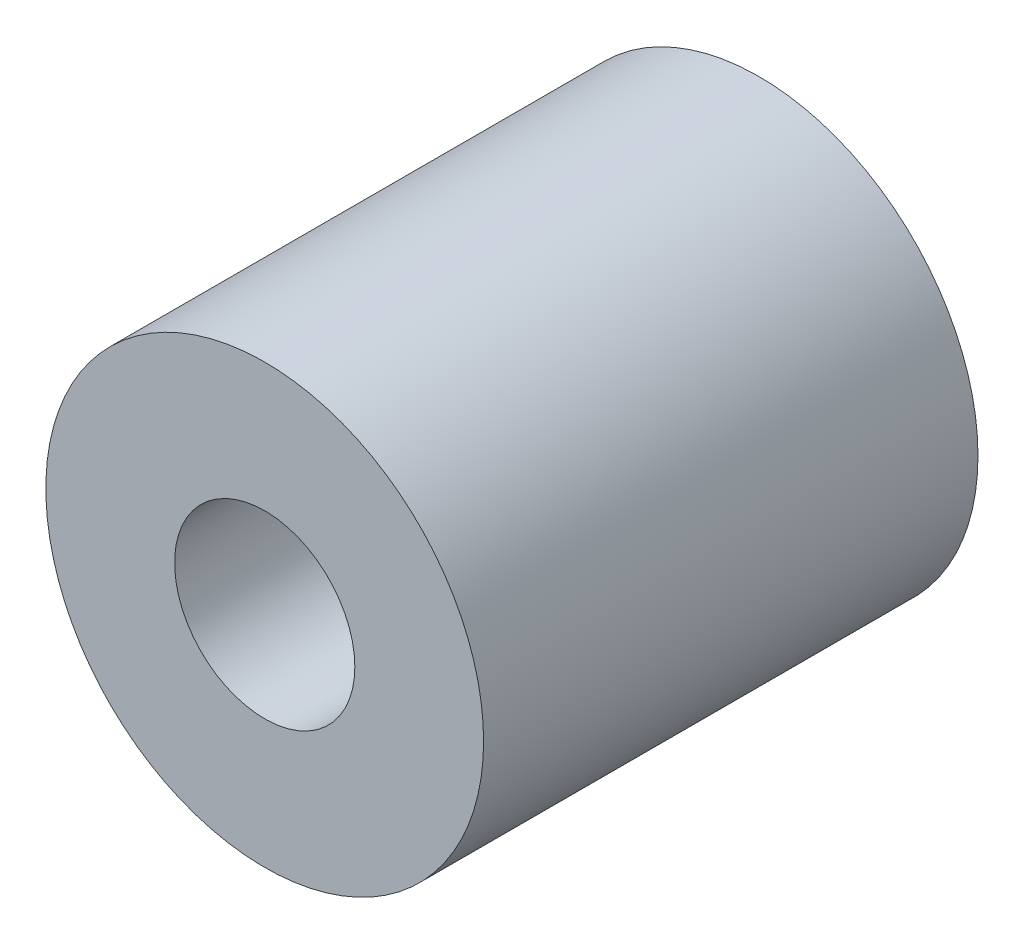
SolidWorks part; units mm, degrees
material "6061-T6 (SS)"
ref_plane "Front Plane" through (0, 0, 0) normal (0, 0, 1) x (1, 0, 0)
ref_plane "Top Plane" through (0, 0, 0) normal (0, 1, 0) x (1, 0, 0)
ref_plane "Right Plane" through (0, 0, 0) normal (1, 0, 0) x (0, 0, -1)
sketch "Sketch1" plane through (0, 0, 0) normal (0, 0, 1) x (1, 0, 0)
  circle A0 centre (0, 0) radius 17
  circle A1 centre (0, 0) radius 3
extrude "D6_Clamp_Hub_Envelope" add sketch "Sketch1" along normal blind 17
sketch "Sketch2" plane through (0, 0, 0) normal (0, 0, 1) x (1, 0, 0)
  circle A0 centre (0, 0) radius 17
  circle A1 centre (0, 0) radius 7
extrude "D14_Hub_And_Disc_Envelope" add sketch "Sketch2" along normal blind 21.4 from offset 17
